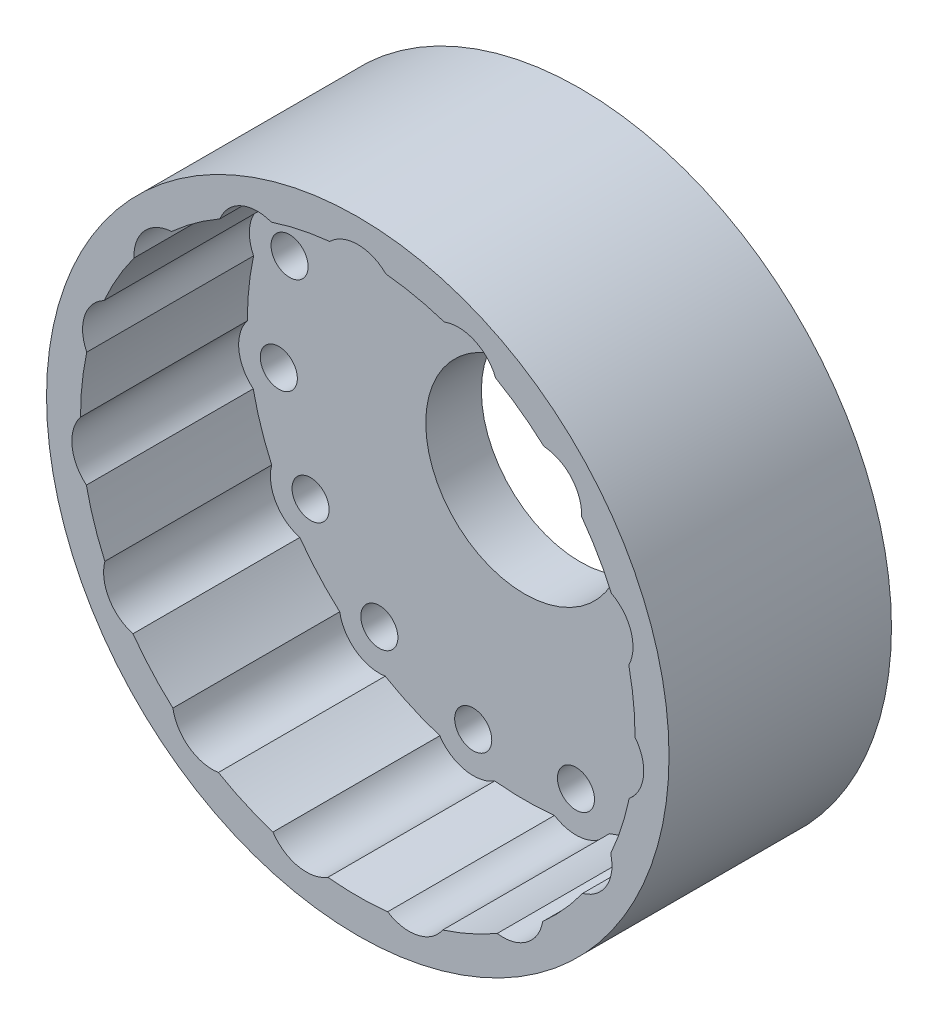
SolidWorks part; units mm, degrees
ref_plane "Front Plane" through (0, 0, 0) normal (0, 0, 1) x (1, 0, 0)
ref_plane "Top Plane" through (0, 0, 0) normal (0, 1, 0) x (1, 0, 0)
ref_plane "Right Plane" through (0, 0, 0) normal (1, 0, 0) x (0, 0, -1)
sketch "Sketch1" plane through (0, 0, 0) normal (0, 0, 1) x (1, 0, 0)
  circle A0 centre (0, 0) radius 40
  circle A1 centre (0, 40) radius 6.5
  circle A2 centre (0, 0) radius 44.875
  circle A3 centre (0, 0) radius 50.375
  dimension "D1" = 80
  dimension "D2" = 13
  dimension "D3" = 0
  dimension "D4" = 4.875
  dimension "D5" = 5.5
extrude "Boss-Extrude1" add sketch "Sketch1" along normal blind 9 contours A1 A0 | A0 A1 | A1 A2 A0 | A1 A2 A0 | A2 A1 | A3 A2 A1
sketch "Sketch2" plane through (0, 0, 9) normal (0, 0, 1) x (1, 0, 0)
  circle A0 centre (0, 0) radius 50.375 construction
  circle A1 centre (0, 0) radius 44.875 construction
  circle A2 centre (0, 40) radius 6.5 construction
  circle A3 centre (0, 0) radius 50.375
  circle A4 centre (0, 0) radius 44.875
  circle A5 centre (0, 40) radius 6.5
  circle A6 centre (16.2695, 36.5418) radius 6.5
  circle A7 centre (29.7258, 26.7652) radius 6.5
  circle A8 centre (38.0423, 12.3607) radius 6.5
  circle A9 centre (39.7809, -4.1811) radius 6.5
  circle A10 centre (34.641, -20) radius 6.5
  circle A11 centre (23.5114, -32.3607) radius 6.5
  circle A12 centre (8.3165, -39.1259) radius 6.5
  circle A13 centre (-8.3165, -39.1259) radius 6.5
  circle A14 centre (-23.5114, -32.3607) radius 6.5
  circle A15 centre (-34.641, -20) radius 6.5
  circle A16 centre (-39.7809, -4.1811) radius 6.5
  circle A17 centre (-38.0423, 12.3607) radius 6.5
  circle A18 centre (-29.7258, 26.7652) radius 6.5
  circle A19 centre (-16.2695, 36.5418) radius 6.5
  point P38 (0, 0)
  circle M6 centre (0, 0) radius 50.375
  dimension "D1" = 15
extrude "Boss-Extrude2" add sketch "Sketch2" along normal blind 27 contours A19 A4 A5 A6 A7 A8 A9 A10 A11 A12 A13 A14 A15 A16 A17 A18 M6
sketch "Sketch3" plane through (0, 0, 9) normal (0, 0, 1) x (1, 0, 0)
  circle A0 centre (0, 40) radius 6.5 construction
  circle A1 centre (0, 40) radius 6.5 construction
  circle A2 centre (0, 40) radius 3
  circle A3 centre (16.2695, 36.5418) radius 3
  circle A4 centre (29.7258, 26.7652) radius 3
  circle A5 centre (38.0423, 12.3607) radius 3
  circle A6 centre (39.7809, -4.1811) radius 3
  circle A7 centre (34.641, -20) radius 3
  circle A8 centre (23.5114, -32.3607) radius 3
  circle A9 centre (8.3165, -39.1259) radius 3
  circle A10 centre (-8.3165, -39.1259) radius 3
  circle A11 centre (-23.5114, -32.3607) radius 3
  circle A12 centre (-34.641, -20) radius 3
  circle A13 centre (-39.7809, -4.1811) radius 3
  circle A14 centre (-38.0423, 12.3607) radius 3
  circle A15 centre (-29.7258, 26.7652) radius 3
  circle A16 centre (-16.2695, 36.5418) radius 3
  point P34 (0, 0)
  dimension "D1" = 6
  dimension "D2" = 15
extrude "Cut-Extrude3" cut sketch "Sketch3" against normal blind 5
sketch "Sketch4" plane through (0, 0, 9) normal (0, 0, 1) x (1, 0, 0)
  circle A0 centre (0, 0) radius 16
  dimension "D1" = 32
extrude "Cut-Extrude4" cut sketch "Sketch4" against normal through all
equation "\"roller_radius\"= 6.5"
equation "\"eccentricity\"= \"roller_radius\" * 0.325"
equation "\"outer_radius\"= 40"
equation "\"eccentric_shaft_radius\"= 16"
equation "\"rotor_width\"= 10"
equation "\"housing_depth\"= 40"
equation "\"bottom_depth\"= 5"
equation "\"roller_bearing_OD\"= \"roller_radius\" * 2"
equation "\"roller_bearing_ID\"= 6"
equation "\"eccentric_bearing_ID\"= 6"
equation "\"eccentric_bearing_OD\"= 15"
equation "\"roller_bearing_height\"= 5"
equation "\"eccentric_bearing_height\"= 5"
equation "\"bottom_bearing_ID\"= 15"
equation "\"bottom_bearing_OD\"= 32"
equation "\"bottom_bearing_height\"= 9"
equation "\"distance_to_output_rotor_holes\"= 20"
equation "\"D1@Sketch1\"=\"outer_radius\"*2"
equation "\"D2@Sketch1\"=\"roller_bearing_OD\""
equation "\"D4@Sketch1\"=\"roller_radius\"*0.75"
equation "\"D1@Sketch3\"=\"roller_bearing_ID\""
equation "\"D1@Sketch4\"=\"bottom_bearing_OD\""
equation "\"D1@Boss-Extrude1\"=\"bottom_bearing_height\""
equation "\"D5@Sketch1\"=\"D1@Sketch1\"*0.06875"
equation "\"output_bearing_ID\" = 25"
equation "\"output_bearing_OD\" = 37"
equation "\"output_bearing_height\" = 7"
equation "\"number_of_rollers\" = 15"
equation "\"housing_height\" = 27"
equation "\"spacer_1\" = 7"
equation "\"spacer_2\" = 2.5"
equation "\"spacer_3\" = 7.5"
equation "\"D1@Boss-Extrude2\"=\"roller_bearing_height\"*2+\"spacer_1\"+\"spacer_2\"+\"spacer_3\""
equation "\"roller_pin_depth\" = 5"
equation "\"D1@Cut-Extrude3\"=\"roller_pin_depth\""
